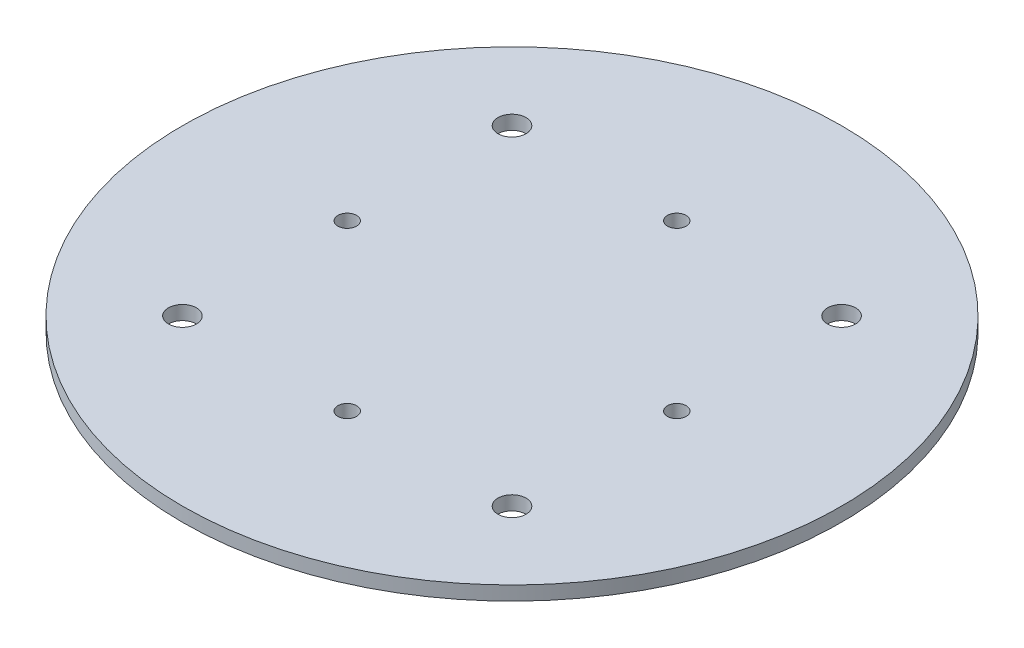
SolidWorks part; units mm, degrees
ref_plane "Front Plane" through (0, 0, 0) normal (0, 0, 1) x (1, 0, 0)
ref_plane "Top Plane" through (0, 0, 0) normal (0, 1, 0) x (1, 0, 0)
ref_plane "Right Plane" through (0, 0, 0) normal (1, 0, 0) x (0, 0, -1)
sketch "Base circle" plane through (0, 0, 0) normal (0, 1, 0) x (1, 0, 0)
  line L0 (0, 70.5) -> (0, -70.5) construction
  line L1 (-70.5, 0) -> (70.5, 0) construction
  circle A0 centre (0, 0) radius 70.5
extrude "Base circle thickness" add sketch "Base circle" along normal blind 3
sketch "Screw holes" plane through (0, 0, 0) normal (0, -1, 0) x (-1, 0, 0)
  line L0 (70.5, 0) -> (35.25, 0) construction
  line L1 (0, 70.5) -> (0, 35.25) construction
  line L2 (-70.5, 0) -> (-35.25, 0) construction
  line L3 (0, -70.5) -> (0, -35.25) construction
  line L4 (35.25, 0) -> (35.25, 35.25) construction
  line L5 (35.25, 35.25) -> (0, 35.25) construction
  line L6 (35.25, 35.25) -> (-35.25, 35.25) construction
  line L8 (35.25, 35.25) -> (35.25, -35.25) construction
  line L9 (35.25, -35.25) -> (-35.25, -35.25) construction
  line L10 (-35.25, 35.25) -> (-35.25, -35.25) construction
  circle A2 centre (0, 0) radius 70.5 construction
  circle A3 centre (35.25, 0) radius 2
  circle A4 centre (0, 35.25) radius 2
  circle A5 centre (-35.25, 0) radius 2
  circle A6 centre (0, -35.25) radius 2
  circle A7 centre (35.25, 35.25) radius 3
  circle A8 centre (35.25, -35.25) radius 3
  circle A9 centre (-35.25, -35.25) radius 3
  circle A10 centre (-35.25, 35.25) radius 3
  point P22 (33.6957, -35.25)
  point P26 (-33.4885, -35.25)
  point P28 (-33.5702, 35.25)
  point P30 (-37.3812, 35.25)
  dimension "D1" = 35.25
  dimension "D2" = 35.25
  dimension "D3" = 70.5
extrude "Base screw drills" cut sketch "Screw holes" against normal blind 3
